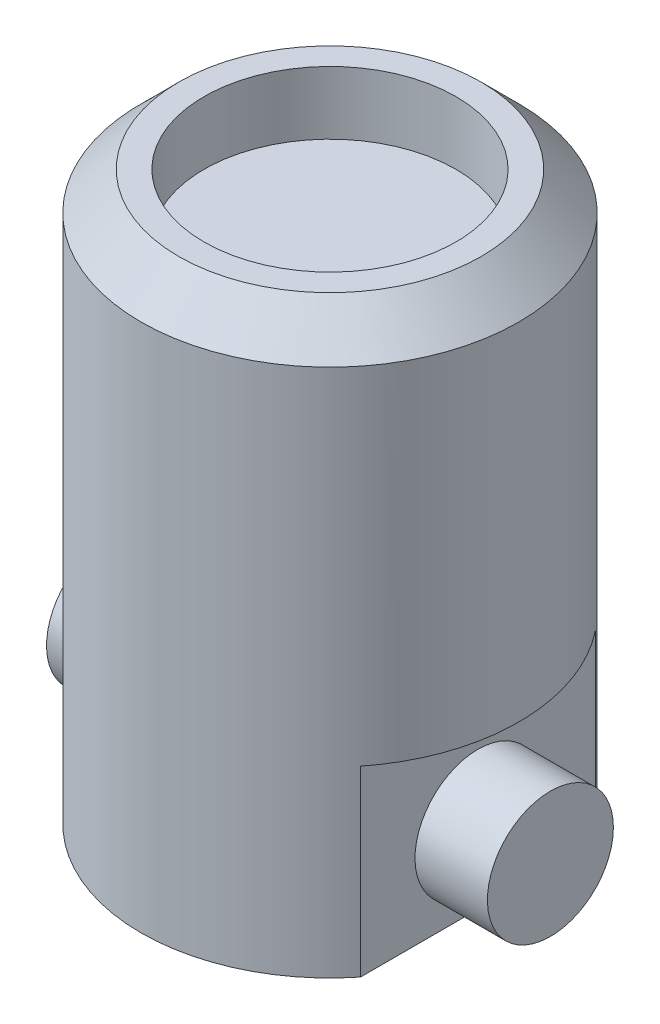
SolidWorks part; units mm, degrees
ref_plane "Front Plane" through (0, 0, 0) normal (0, 0, 1) x (1, 0, 0)
ref_plane "Top Plane" through (0, 0, 0) normal (0, 1, 0) x (1, 0, 0)
ref_plane "Right Plane" through (0, 0, 0) normal (1, 0, 0) x (0, 0, -1)
sketch "Sketch1" plane through (0, 0, 0) normal (0, 1, 0) x (1, 0, 0)
  circle A0 centre (0, 0) radius 30
  dimension "D1" = 60
extrude "Boss-Extrude1" add sketch "Sketch1" along normal blind 90
sketch "Sketch2" plane through (0, 0, 0) normal (0, 0, 1) x (1, 0, 0)
  line L0 (-30, 29) -> (-23.5, 29)
  line L1 (-30, 90) -> (-30, 0) construction
  line L2 (-23.5, 29) -> (-23.5, 0)
  line L3 (-30, 0) -> (30, 0) construction
  dimension "D1" = 6.5
  dimension "D2" = 29
extrude "Cut-Extrude3" cut sketch "Sketch2" against normal through all and the other way through all flip side to cut
mirror "Mirror1" about plane through (0, 0, 0) normal (1, 0, 0) of "Cut-Extrude3"
sketch "Sketch4" plane through (0, 0, 0) normal (1, 0, 0) x (0, 0, -1)
  circle A0 centre (0, 12) radius 10
  dimension "D1" = 20
  dimension "D2" = 12
extrude "Boss-Extrude2" add sketch "Sketch4" along normal mid plane 70
sketch "Sketch5" plane through (0, 90, 0) normal (0, 1, 0) x (1, 0, 0)
  circle A0 centre (0, 0) radius 20
  dimension "D1" = 40
extrude "Cut-Extrude4" cut sketch "Sketch5" against normal blind 10
chamfer "Chamfer1" distance 6 angle 45 1 edges at (0, 90, 30)
